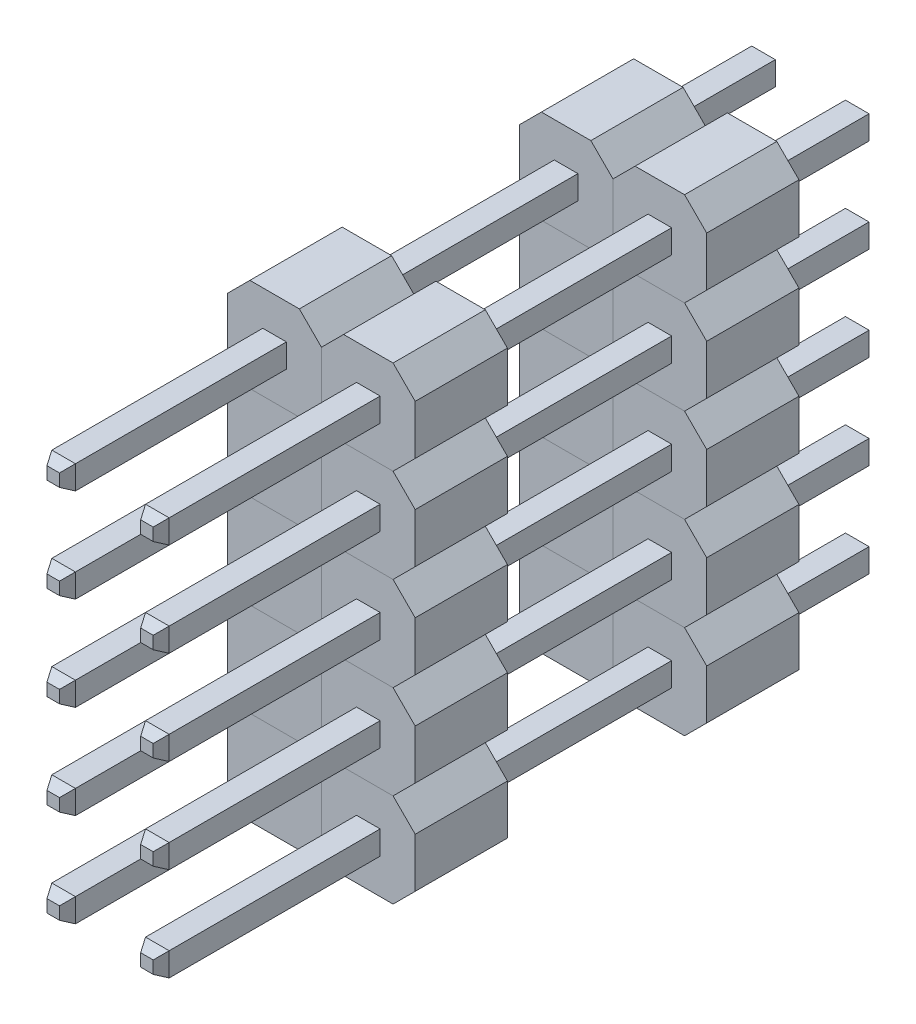
SolidWorks part; units mm, degrees
ref_plane "Спереди" through (0, 0, 0) normal (0, 0, 1) x (1, 0, 0)
ref_plane "Сверху" through (0, 0, 0) normal (0, 1, 0) x (1, 0, 0)
ref_plane "Справа" through (0, 0, 0) normal (1, 0, 0) x (0, 0, -1)
sketch "Эскиз1" plane through (0, 0, 0) normal (0, 0, 1) x (1, 0, 0)
  line L1 (-2.54, -6.35) -> (0, -6.35)
  line L2 (-2.54, -6.35) -> (-2.54, -3.81)
  line L3 (-2.54, -3.81) -> (0, -3.81)
  line L4 (0, -6.35) -> (0, -3.81)
  line L5 (0, -9.779) -> (0, 9.779) construction
  line L6 (-2.54, -6.35) -> (0, -3.81) construction
  point P0 (0, 0)
  point P6 (-1.27, -5.08)
  dimension "D1" = 2.54
  dimension "D2" = 5.08
extrude "Бобышка-Вытянуть1" add sketch "Эскиз1" along normal blind 2.5
ref_plane "Плоскость1" through (0, 0, 10.4) normal (0, 0, 1) x (1, 0, 0)
sketch "Эскиз3" plane through (0, 0, 10.4) normal (0, 0, 1) x (1, 0, 0)
  line L1 (-2.54, -3.81) -> (0, -3.81)
  line L2 (-2.54, -3.81) -> (-2.54, -6.35)
  line L3 (-2.54, -6.35) -> (0, -6.35)
  line L4 (0, -3.81) -> (0, -6.35)
  line L5 (-2.54, -3.81) -> (0, -6.35) construction
  line L6 (-2.54, -6.35) -> (0, -3.81) construction
  point P0 (-1.27, -5.08)
  point P5 (0, 0)
  point P7 (0, 0)
extrude "Бобышка-Вытянуть3" add sketch "Эскиз3" against normal blind 2.5
chamfer "Фаска1" distance 0.6 angle 45 4 edges at (-2.54, -3.81, 1.25) (-2.54, -6.35, 1.25) (0, -6.35, 1.25) (0, -3.81, 1.25)
chamfer "Фаска3" distance 0.6 angle 45 4 edges at (-2.54, -3.81, 9.15) (0, -3.81, 9.15) (0, -6.35, 9.15) (-2.54, -6.35, 9.15)
sketch "Эскиз2" plane through (0, 0, 0) normal (0, 0, -1) x (-1, 0, 0)
  line L0 (1.59, -5.4) -> (0.95, -4.76) construction
  line L1 (1.59, -5.4) -> (0.95, -5.4)
  line L2 (1.59, -5.4) -> (1.59, -4.76)
  line L3 (1.59, -4.76) -> (0.95, -4.76)
  line L4 (0.95, -5.4) -> (0.95, -4.76)
  line L5 (0.95, -5.4) -> (1.59, -4.76) construction
  line L7 (2.54, -6.35) -> (0, -3.81) construction
  point P8 (1.27, -5.08)
  point P11 (1.27, -5.08)
  dimension "D1" = 0.64
extrude "Бобышка-Вытянуть2" add sketch "Эскиз2" along normal blind 3 and the other way blind 16.4
chamfer "Фаска2" distance 0.15 angle 62 8 edges at (-1.59, -5.08, -3) (-1.27, -4.76, -3) (-0.95, -5.08, -3) (-1.27, -5.4, -3) (-1.27, -4.76, 16.4) (-0.95, -5.08, 16.4) (-1.27, -5.4, 16.4) (-1.59, -5.08, 16.4)
pattern_linear "Линейный массив5" count 2 spacing 2.54 along (1, 0, 0) count 5 spacing 2.54 along (0, 1, 0) of "Бобышка-Вытянуть1", "Бобышка-Вытянуть2", "Фаска2"
equation "\"N\"= 10"
equation "\"D2@Линейный массив3\"=\"N\"/2"
equation "\"D2@Линейный массив5\"=\"N\"/2"
equation "\"D2@Эскиз1\"=((\"N\"/2)-1)/2*2.54"
